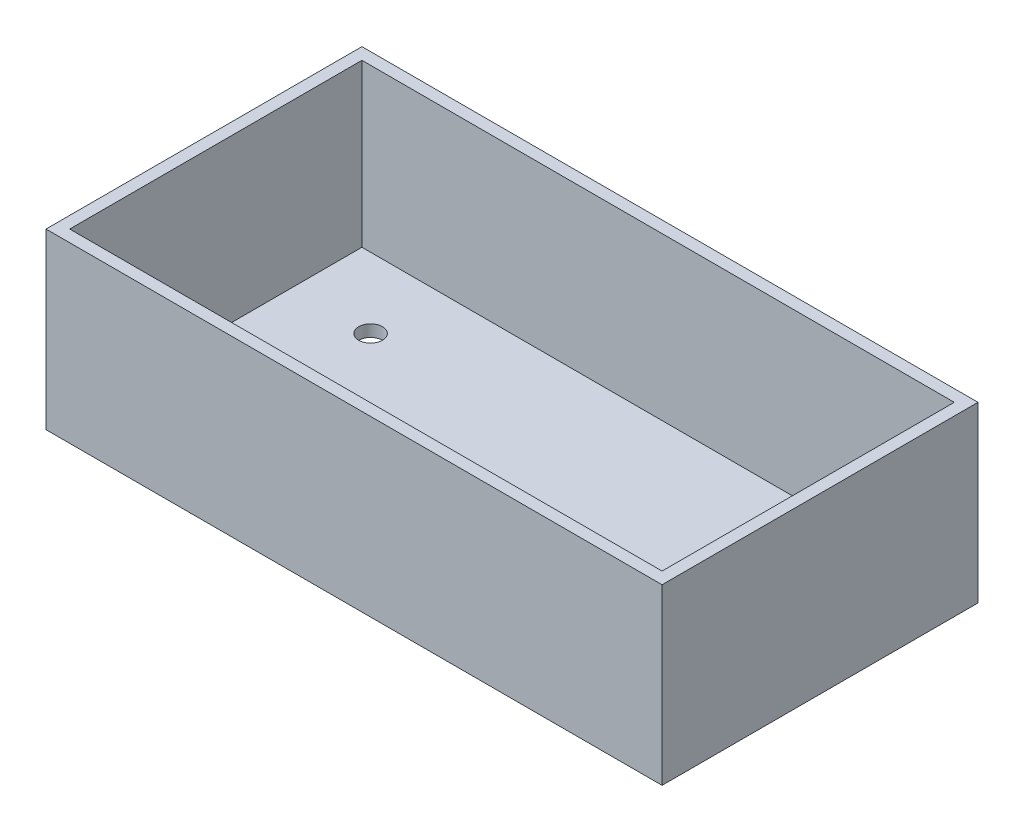
SolidWorks part; units mm, degrees
ref_plane "Front Plane" through (0, 0, 0) normal (0, 0, 1) x (1, 0, 0)
ref_plane "Top Plane" through (0, 0, 0) normal (0, 1, 0) x (1, 0, 0)
ref_plane "Right Plane" through (0, 0, 0) normal (1, 0, 0) x (0, 0, -1)
sketch "Sketch1" plane through (0, 0, 0) normal (0, 1, 0) x (1, 0, 0)
  line L1 (-39, -20) -> (39, -20)
  line L2 (-39, -20) -> (-39, 20)
  line L3 (-39, 20) -> (39, 20)
  line L4 (39, -20) -> (39, 20)
  line L5 (-39, -20) -> (39, 20) construction
  line L6 (-39, 20) -> (39, -20) construction
  point P0 (0, 0)
  dimension "D1" = 78
  dimension "D2" = 40
extrude "Boss-Extrude1" add sketch "Sketch1" along normal blind 22
shell "Shell1" thickness 1.5
sketch "Sketch2" plane through (0, 0, 0) normal (0, -1, 0) x (1, 0, 0)
  line L1 (27.5, 9.6) -> (-27.5, 9.6) construction
  line L2 (27.5, 9.6) -> (27.5, -9.6) construction
  line L3 (27.5, -9.6) -> (-27.5, -9.6) construction
  line L4 (-27.5, 9.6) -> (-27.5, -9.6) construction
  line L5 (27.5, 9.6) -> (-27.5, -9.6) construction
  line L6 (27.5, -9.6) -> (-27.5, 9.6) construction
  circle A0 centre (27.5, 9.6) radius 1.5
  circle A1 centre (27.5, -9.6) radius 1.5
  circle A2 centre (-27.5, -9.6) radius 1.5
  circle A3 centre (-27.5, 9.6) radius 1.5
  point P0 (0, 0)
  dimension "D1" = 3
  dimension "D2" = 55
  dimension "D3" = 19.2
extrude "Cut-Extrude1" cut sketch "Sketch2" against normal through all
